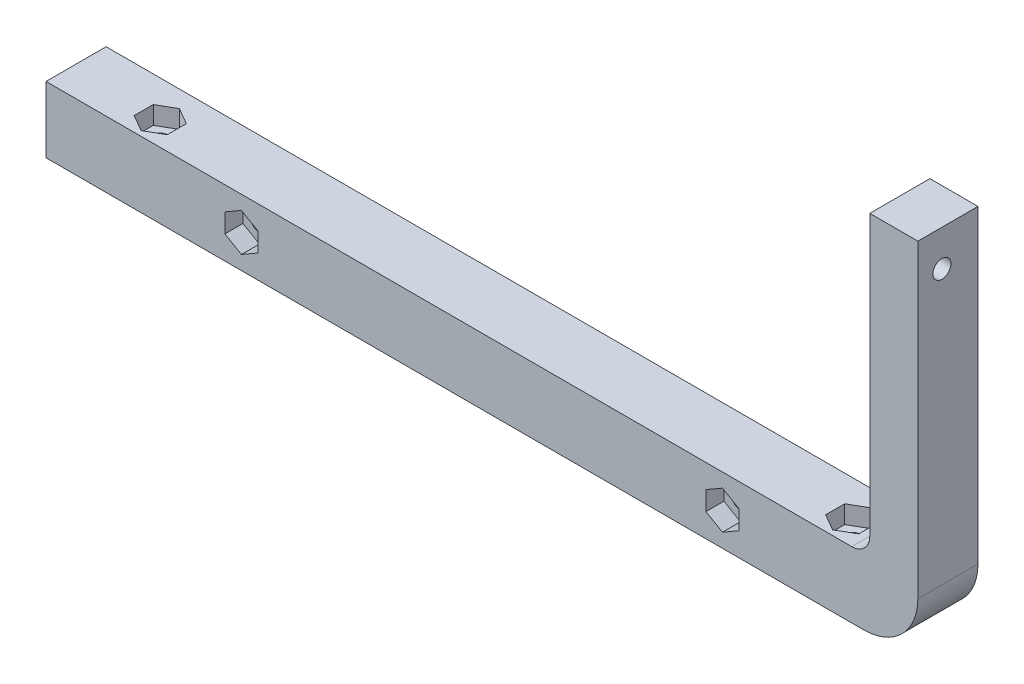
SolidWorks part; units mm, degrees
material "ABS"
ref_plane "Front" through (0, 0, 0) normal (0, 0, 1) x (1, 0, 0)
ref_plane "Top" through (0, 0, 0) normal (0, 1, 0) x (1, 0, 0)
ref_plane "Right" through (0, 0, 0) normal (1, 0, 0) x (0, 0, -1)
sketch "Esquisse1" plane through (0, 0, 0) normal (0, 1, 0) x (1, 0, 0)
  line L1 (-72.5, 10) -> (72.5, 10)
  line L2 (-72.5, 10) -> (-72.5, 0)
  line L3 (-72.5, 0) -> (72.5, 0)
  line L4 (72.5, 10) -> (72.5, 0)
  dimension "D1" = 10
  dimension "D2" = 145
extrude "Boss.-Extru.1" add sketch "Esquisse1" along normal blind 11
sketch "Esquisse2" plane through (0, 11, 0) normal (0, 1, 0) x (1, 0, 0)
  line L2 (72.5, 10) -> (-72.5, 10) construction
  circle A0 centre (-57.5, 4) radius 1.5
  circle A1 centre (0, 4) radius 1.5 construction
  circle A2 centre (57.5, 4) radius 1.5
  dimension "D1" = 3
  dimension "D2" = 3
  dimension "D3" = 57.5
  dimension "D4" = 6
extrude "Enlèv. mat.-Extru.1" cut sketch "Esquisse2" against normal through all
sketch "Esquisse3" plane through (0, 0, 0) normal (0, 0, 1) x (1, 0, 0)
  line L0 (-72.5, 11) -> (-72.5, 0) construction
  line L1 (0, -50) -> (0, 50) construction
  circle A0 centre (-40, 5.5) radius 1.5
  circle A1 centre (40, 5.5) radius 1.5
  point P4 (-72.5, 5.5)
  dimension "D1" = 3
  dimension "D2" = 80
extrude "Enlèv. mat.-Extru.2" cut sketch "Esquisse3" against normal through all
sketch "Esquisse4" plane through (0, 0, 0) normal (0, 0, 1) x (1, 0, 0)
  line L1 (-37.25, 7.0877) -> (-40, 8.6754)
  line L2 (-40, 8.6754) -> (-42.75, 7.0877)
  line L3 (-42.75, 7.0877) -> (-42.75, 3.9123)
  line L4 (-42.75, 3.9123) -> (-40, 2.3246)
  line L5 (-40, 2.3246) -> (-37.25, 3.9123)
  line L6 (-37.25, 3.9123) -> (-37.25, 7.0877)
  line L7 (42.75, 7.0877) -> (40, 8.6754)
  line L8 (40, 8.6754) -> (37.25, 7.0877)
  line L9 (37.25, 7.0877) -> (37.25, 3.9123)
  line L10 (37.25, 3.9123) -> (40, 2.3246)
  line L11 (40, 2.3246) -> (42.75, 3.9123)
  line L12 (42.75, 3.9123) -> (42.75, 7.0877)
  circle A4 centre (-40, 5.5) radius 2.75 construction
  circle A5 centre (40, 5.5) radius 2.75 construction
  dimension "D1" = 5.5
extrude "Enlèv. mat.-Extru.3" cut sketch "Esquisse4" against normal blind 3
sketch "Esquisse5" plane through (0, 11, 0) normal (0, 1, 0) x (1, 0, 0)
  line L1 (-54.75, 5.5877) -> (-57.5, 7.1754)
  line L2 (-57.5, 7.1754) -> (-60.25, 5.5877)
  line L3 (-60.25, 5.5877) -> (-60.25, 2.4123)
  line L4 (-60.25, 2.4123) -> (-57.5, 0.8246)
  line L5 (-57.5, 0.8246) -> (-54.75, 2.4123)
  line L6 (-54.75, 2.4123) -> (-54.75, 5.5877)
  line L13 (60.25, 5.5877) -> (57.5, 7.1754)
  line L14 (57.5, 7.1754) -> (54.75, 5.5877)
  line L15 (54.75, 5.5877) -> (54.75, 2.4123)
  line L16 (54.75, 2.4123) -> (57.5, 0.8246)
  line L17 (57.5, 0.8246) -> (60.25, 2.4123)
  line L18 (60.25, 2.4123) -> (60.25, 5.5877)
  circle A0 centre (-57.5, 4) radius 2.75 construction
  circle A2 centre (57.5, 4) radius 2.75 construction
  dimension "D1" = 5.5
extrude "Enlèv. mat.-Extru.4" cut sketch "Esquisse5" against normal blind 3
fillet "Congé1" radius 9 1 edges at (72.5, 0, -5)
sketch "Esquisse6" plane through (0, 11, 0) normal (0, 1, 0) x (1, 0, 0)
  line L0 (-72.5, 0) -> (72.5, 0) construction
  line L1 (72.5, 10) -> (64.5, 10)
  line L2 (72.5, 10) -> (72.5, 0)
  line L3 (72.5, 0) -> (64.5, 0)
  line L4 (64.5, 10) -> (64.5, 0)
  dimension "D1" = 8
extrude "Boss.-Extru.2" add sketch "Esquisse6" along normal blind 49.5
fillet "Congé2" radius 3 1 edges at (64.5, 11, -5)
sketch "Esquisse7" plane through (72.5, 0, 0) normal (1, 0, 0) x (0, 0, -1)
  line L0 (10, 60.5) -> (10, 9) construction
  line L1 (0, 60.5) -> (10, 60.5) construction
  circle A0 centre (4, 54.5) radius 1.5
  dimension "D1" = 6
  dimension "D2" = 6
  dimension "D3" = 3
extrude "Enlèv. mat.-Extru.5" cut sketch "Esquisse7" against normal through all
sketch "Esquisse8" plane through (64.5, 0, 0) normal (-1, 0, 0) x (0, 0, 1)
  line L1 (-0.8246, 54.5) -> (-2.4123, 57.25)
  line L2 (-2.4123, 57.25) -> (-5.5877, 57.25)
  line L3 (-5.5877, 57.25) -> (-7.1754, 54.5)
  line L4 (-7.1754, 54.5) -> (-5.5877, 51.75)
  line L5 (-5.5877, 51.75) -> (-2.4123, 51.75)
  line L6 (-2.4123, 51.75) -> (-0.8246, 54.5)
  circle A0 centre (-4, 54.5) radius 2.75 construction
  dimension "D1" = 5.5
extrude "Enlèv. mat.-Extru.6" cut sketch "Esquisse8" against normal blind 3
sketch "Esquisse9" plane through (0, 0, -10) normal (0, 0, -1) x (-1, 0, 0)
  line L6 (-72.5, 60.5) -> (-72.5, 9)
  line L7 (-63.5, 0) -> (72.5, 0)
  line L8 (72.5, 0) -> (72.5, 11)
  line L9 (72.5, 11) -> (-61.5, 11)
  line L10 (-64.5, 14) -> (-64.5, 60.5)
  line L11 (-64.5, 60.5) -> (-72.5, 60.5)
  line L12 (-72.5, 60.5) -> (-72.5, 9)
  line L13 (-63.5, 0) -> (72.5, 0)
  line L14 (72.5, 0) -> (72.5, 11)
  line L15 (72.5, 11) -> (-61.5, 11)
  line L16 (-64.5, 14) -> (-64.5, 60.5)
  line L17 (-64.5, 60.5) -> (-72.5, 60.5)
  arc A2 (-72.5, 9) -> (-63.5, 0) centre (-63.5, 9) ccw
  arc A3 (-64.5, 14) -> (-61.5, 11) centre (-61.5, 14) ccw
  arc A4 (-72.5, 9) -> (-63.5, 0) centre (-63.5, 9) ccw
  arc A5 (-64.5, 14) -> (-61.5, 11) centre (-61.5, 14) ccw
  dimension "D1" = 0
extrude "Boss.-Extru.3" add sketch "Esquisse9" against normal blind 0.2
